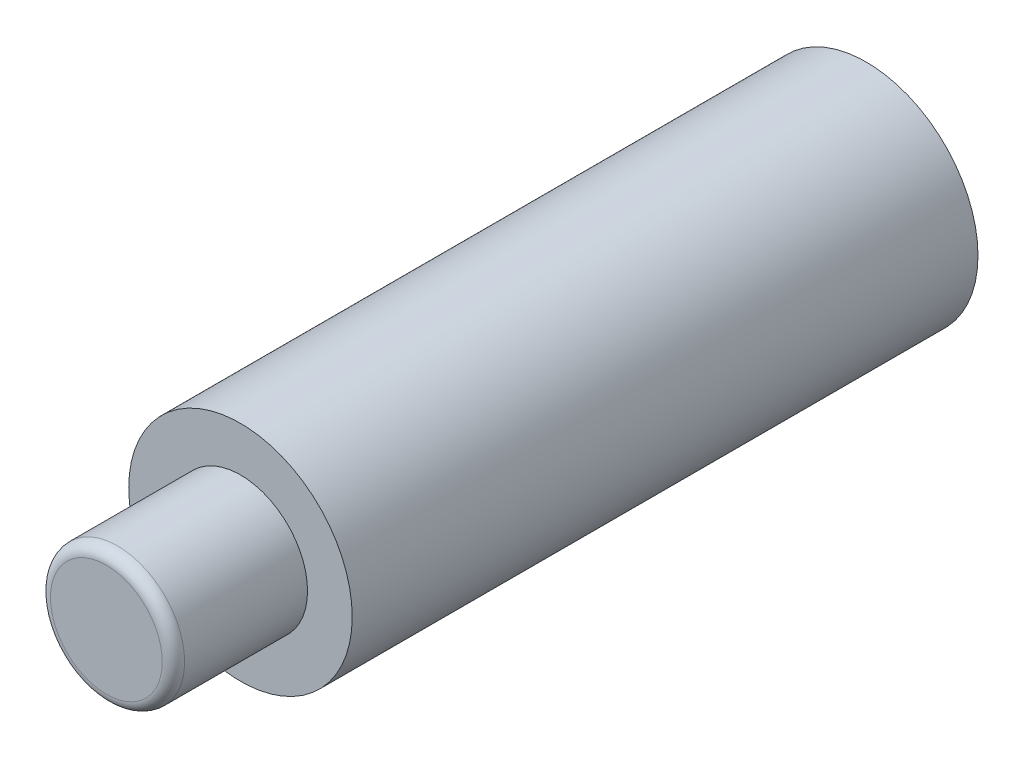
SolidWorks part; units mm, degrees
ref_plane "정면" through (0, 0, 0) normal (0, 0, 1) x (1, 0, 0)
ref_plane "윗면" through (0, 0, 0) normal (0, 1, 0) x (1, 0, 0)
ref_plane "우측면" through (0, 0, 0) normal (1, 0, 0) x (0, 0, -1)
sketch "스케치1" plane through (0, 0, 0) normal (0, 0, 1) x (1, 0, 0)
  circle A0 centre (0, 0) radius 25
  dimension "D1" = 50
extrude "보스-돌출1" add sketch "스케치1" along normal blind 140
sketch "스케치2" plane through (0, 0, 140) normal (0, 0, 1) x (1, 0, 0)
  circle A0 centre (0, 0) radius 15
  dimension "D1" = 30
extrude "보스-돌출2" add sketch "스케치2" along normal blind 30
fillet "필렛1" radius 2.5 1 edges at (15, 0, 170)
